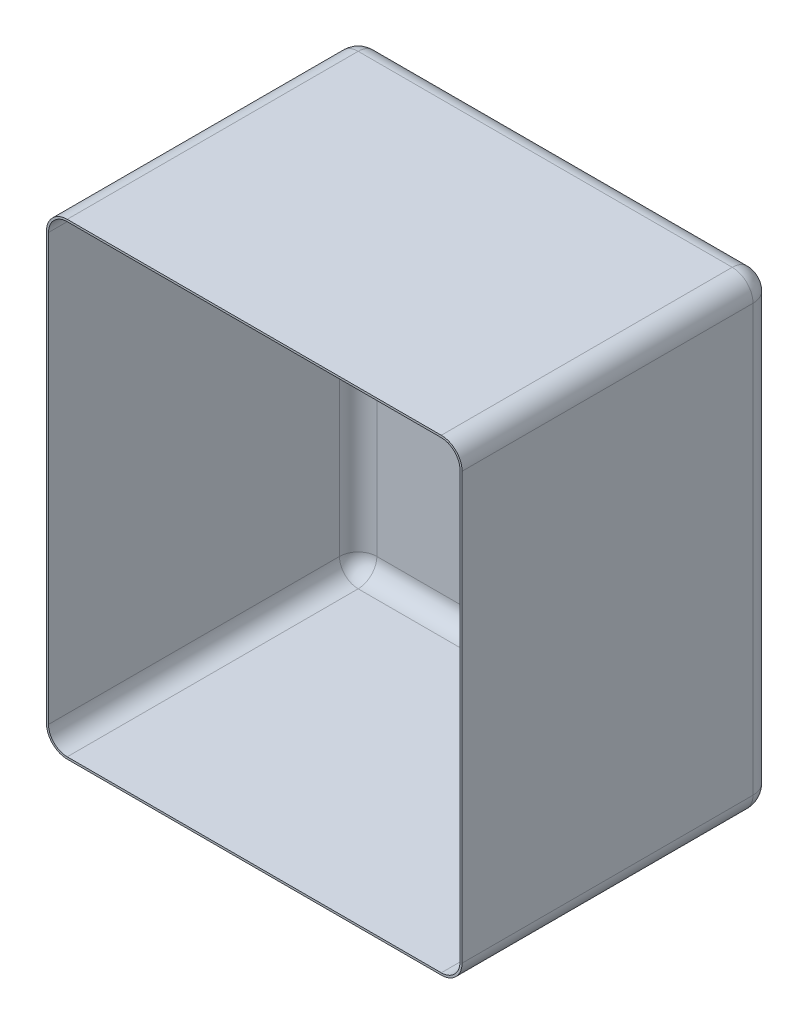
SolidWorks part; units mm, degrees
material "ABS"
ref_plane "Ebene vorne" through (0, 0, 0) normal (0, 0, 1) x (1, 0, 0)
ref_plane "Ebene oben" through (0, 0, 0) normal (0, 1, 0) x (1, 0, 0)
ref_plane "Ebene rechts" through (0, 0, 0) normal (1, 0, 0) x (0, 0, -1)
sketch "Skizze1" plane through (0, 0, 0) normal (0, 0, 1) x (1, 0, 0)
  line L1 (-200, 225) -> (200, 225)
  line L2 (-200, 225) -> (-200, -225)
  line L3 (-200, -225) -> (200, -225)
  line L4 (200, 225) -> (200, -225)
  line L5 (-200, 225) -> (200, -225) construction
  line L6 (-200, -225) -> (200, 225) construction
  point P0 (0, 0)
  dimension "D1" = 450
  dimension "D2" = 400
extrude "Aufsatz-Linear austragen1" add sketch "Skizze1" along normal blind 300
fillet "Verrundung2" radius 20 8 edges at (0, 225, 0) (-200, 0, 0) (0, -225, 0) (200, 0, 0) (-200, 225, 150) (-200, -225, 150) (200, 225, 150) (200, -225, 150)
shell "Wandung1" thickness 2
